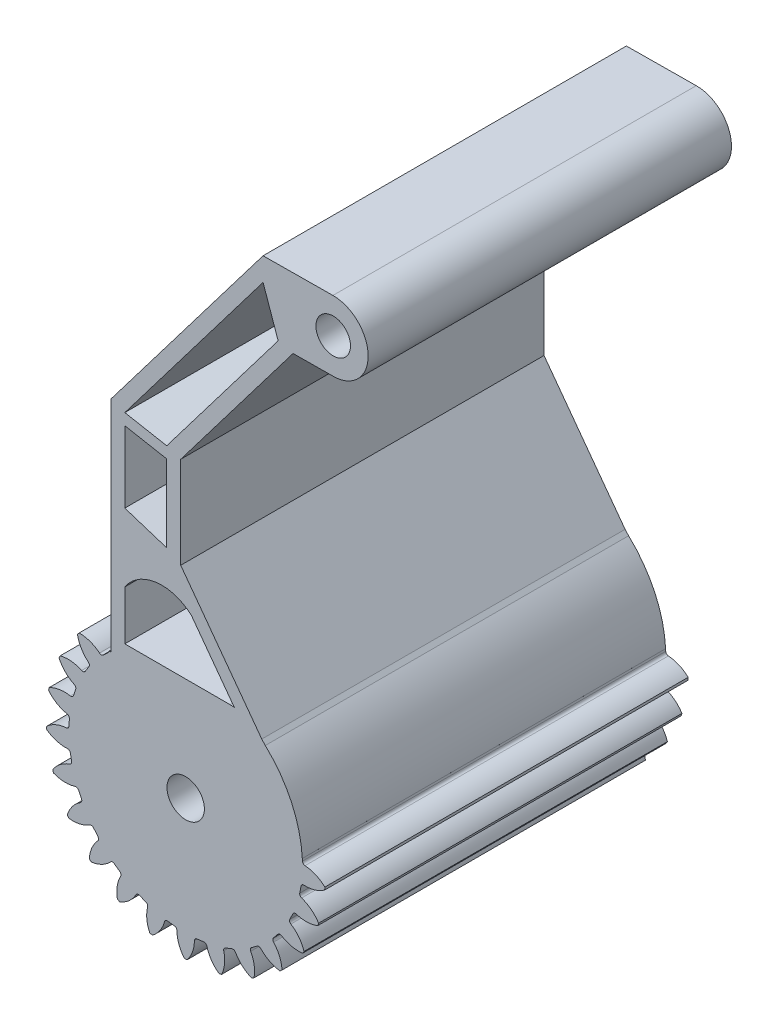
SolidWorks part; units mm, degrees
material "ABS"
ref_plane "Front Plane" through (0, 0, 0) normal (0, 0, 1) x (1, 0, 0)
ref_plane "Top Plane" through (0, 0, 0) normal (0, 1, 0) x (1, 0, 0)
ref_plane "Right Plane" through (0, 0, 0) normal (1, 0, 0) x (0, 0, -1)
sketch "Sketch1" plane through (0, 0, 0) normal (0, 0, 1) x (1, 0, 0)
  circle A0 centre (0, 0) radius 10.625
  circle A1 centre (0, 0) radius 11.475
  circle A2 centre (0, 0) radius 12.665
  dimension "D1" = 21.25
  dimension "D2" = 22.95
  dimension "D4" = 25.33
  dimension "D3" = 2.04
  dimension "D5" = 1.19
extrude "Boss-Extrude1" add sketch "Sketch1" along normal mid plane 33.02 contours A2
sketch "Sketch3" plane through (0, 0, 0) normal (0, 0, 1) x (1, 0, 0)
  line L0 (0, 0) -> (0, 31.9299) construction
  line L1 (-0.7205, 11.4524) -> (0.7205, 11.4524) construction
  line L2 (-0.5496, 10.6108) -> (0, 0) construction
  line L3 (0, 9.4727) -> (-7.4091, 29.8291) construction
  line L4 (-0.5496, 10.6108) -> (0.5496, 10.6108)
  line L5 (0, 0) -> (4.4013, 34.8396) construction
  line L6 (0.7205, 11.4524) -> (2.1502, 11.2717) construction
  arc A0 (-0.5496, 10.6108) -> (-3.0161, 13.328) centre (-3.4447, 10.4608) ccw
  arc A1 (0.5496, 10.6108) -> (3.0161, 13.328) centre (3.4447, 10.4608) cw
  circle A2 centre (0, 0) radius 10.625 construction
  circle A4 centre (0, 0) radius 11.475 construction
  circle A5 centre (0, 0) radius 13.665
  arc A6 (3.0161, 13.328) -> (-3.0161, 13.328) centre (0, 0) ccw
  dimension "D2" = 20
  dimension "D3" = 7.2
  dimension "D1" = 1
extrude "Cut-Extrude1" cut sketch "Sketch3" against normal through all both and the other way through all
fillet "Fillet1" radius 0.255 2 edges at (0.5496, 10.6108, 0) (-0.5496, 10.6108, 0)
pattern_circular "CirPattern1" count 25 over 360 about axis through (0, 0, 16.51) along (0, 0, 1) skipping 1, 2, 20, 21, 22, 23, 24 of "Fillet1", "Cut-Extrude1"
sketch "Sketch4" plane through (0, 0, 16.51) normal (0, 0, 1) x (1, 0, 0)
  point P0 (0, 0)
hole_wizard "M3 Clearance Hole1" positions "Sketch5" profile "Sketch6" hole size "M3" standard "ANSI Metric" end condition through all
sketch "Sketch5" plane through (0, 0, 16.51) normal (0, 0, 1) x (1, 0, 0)
  point P0 (0, 0)
sketch "Sketch6" plane through (0, 0, 16.51) normal (1, 0, 0) x (0, -1, 0)
  line L0 (0, 0) -> (0, 33.02)
  line L1 (0, 33.02) -> (1.7, 33.02)
  line L2 (1.7, 33.02) -> (1.7, 0)
  line L5 (1.7, 0) -> (0, 0)
  line L11 (0, -6.35) -> (0, 107.95) construction
  dimension "Thru Hole Dia." = 3.4
  dimension "Thru Hole Depth" = 33.02
sketch "Sketch7" plane through (0, 0, 16.51) normal (0, 0, 1) x (1, 0, 0)
  line L1 (-7.669, 8.1096) -> (7.764, 8.1096)
  line L2 (-7.669, 8.1096) -> (-7.669, 13.4958)
  line L3 (-7.669, 13.4958) -> (7.764, 13.4958)
  line L4 (7.764, 8.1096) -> (7.764, 13.4958)
  dimension "D1" = 8.1096
extrude "Cut-Extrude2" cut sketch "Sketch7" against normal through all
sketch "Sketch8" plane through (0, 0, 0) normal (0, 0, 1) x (1, 0, 0)
  line L0 (3.993, 8.1096) -> (-6.8025, 8.1096)
  line L1 (-6.8025, 8.1096) -> (-6.8025, 28.0115)
  line L2 (-6.8025, 28.0115) -> (7.0326, 46.2096)
  line L3 (7.0326, 46.2096) -> (13.3826, 46.2624)
  line L4 (-6.9538, 8.1096) -> (7.764, 8.1096) construction
  line L5 (13.4355, 39.9126) -> (9.7599, 39.882)
  line L6 (9.7599, 39.882) -> (-0.4525, 26.4492)
  line L7 (-0.4525, 26.4492) -> (-0.4525, 18.1053)
  line L8 (-0.4525, 18.1053) -> (7.0326, 7.9518)
  line L9 (7.0326, 7.9518) -> (7.0326, 60.6555) construction
  line L10 (3.993, 8.1096) -> (7.0326, 7.9518)
  line L11 (3.993, 8.1096) -> (10.4812, -0.877) construction
  line L12 (10.4812, -0.877) -> (7.0326, 7.9518) construction
  line L13 (-6.9538, 8.1096) -> (7.764, 8.1096) construction
  line L14 (-5.5325, 9.3796) -> (-5.5325, 13.8625)
  line L15 (-5.5325, 27.5836) -> (7.0326, 44.1111)
  line L18 (8.4051, 40.1986) -> (-1.7225, 26.8772)
  line L19 (-1.7225, 25.8439) -> (-1.7225, 18.8403)
  line L20 (0.5315, 14.6303) -> (4.4173, 9.3593)
  line L21 (4.0259, 9.3796) -> (4.4173, 9.3593)
  line L22 (4.0259, 9.3796) -> (-5.5325, 9.3796)
  line L23 (-5.5325, 27.5836) -> (-1.7225, 26.8772)
  line L25 (-5.5325, 20.0641) -> (-1.7225, 18.8403)
  line L26 (-5.5325, 26.5503) -> (-1.7225, 25.8439)
  line L27 (-5.5325, 20.0641) -> (-5.5325, 26.5503)
  line L28 (7.0326, 44.1111) -> (8.4051, 40.1986)
  line L29 (-5.5325, 9.3796) -> (-5.5325, 27.5836) construction
  line L30 (-1.7225, 17.6878) -> (4.4173, 9.3593) construction
  line L31 (-1.7225, 26.8772) -> (-1.7225, 17.6878) construction
  line L33 (9.1261, 41.1468) -> (-1.7225, 26.8772) construction
  line L34 (-5.5325, 27.5836) -> (7.6664, 44.9448) construction
  line L35 (13.4249, 41.1826) -> (9.1261, 41.1468) construction
  line L36 (7.6664, 44.9448) -> (13.3932, 44.9925) construction
  arc A0 (13.3826, 46.2624) -> (13.4355, 39.9126) centre (13.4091, 43.0875) cw
  arc A2 (-5.5325, 13.8625) -> (0.5315, 14.6303) centre (-2.1737, 11.6656) cw
  circle A3 centre (13.4091, 43.0875) radius 1.57
  arc A4 (13.3932, 44.9925) -> (13.4249, 41.1826) centre (13.4091, 43.0875) cw construction
  point P37 (7.0174, 44.0975)
  dimension "D7" = 3.175
  dimension "D15" = 3.14
  dimension "D1" = 38.1
  dimension "D2" = 22.86
  dimension "D3" = 6.35
  dimension "D4" = 6.35
  dimension "D5" = 6.35
  dimension "D6" = 31.9303
  dimension "D8" = 3.0397
  dimension "D9" = 2.7272
  dimension "D10" = 18.0845
  dimension "D11" = 9.7519
  dimension "D12" = 1.27
  dimension "D13" = 1.016
  dimension "D14" = 2.286
extrude "claw part" add sketch "Sketch8" along normal through all and the other way through all
sketch "Sketch9" plane through (0, 0, 16.51) normal (0, 0, 1) x (1, 0, 0)
  line L0 (6.9163, 8.1096) -> (7.2347, 7.7619)
  line L1 (6.9163, 8.1096) -> (7.9569, 10.6945)
  line L2 (7.9569, 10.6945) -> (13.7606, 4.4328)
  line L3 (13.7606, 4.4328) -> (13.5131, 1.9702)
  line L4 (13.5131, 1.9702) -> (10.5964, 0.5525)
  arc A0 (10.5964, 0.5525) -> (7.2347, 7.7619) centre (0, 0) ccw
extrude "Cut-Extrude3" cut sketch "Sketch9" against normal through all
sketch "Sketch10" plane through (0, 0, 16.51) normal (0, 0, 1) x (1, 0, 0)
  circle A0 centre (0, 0) radius 12.665
equation "\"module\"= 0.85mm"
equation "\"number of teeth\"= 25"
equation "\"D1@Sketch1\"=\"module\"*\"number of teeth\""
equation "\"D2@Sketch1\"=(\"number of teeth\"+2)*(\"module\")"
equation "\"D3@Sketch1\"=\"module\"*if(\"module\"=>1.25,2.25,2.4)"
equation "\"D3@Sketch3\"=180/\"number of teeth\""
equation "\"D1@Fillet1\"=.3*\"module\""
equation "\"D1@CirPattern1\"=\"number of teeth\""
